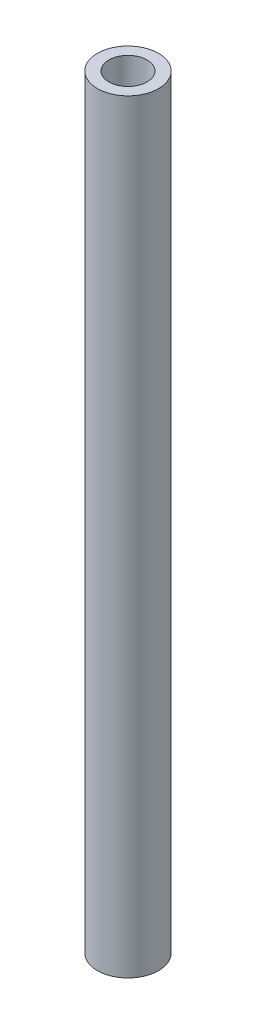
SolidWorks part; units mm, degrees
material "Thornel Mat VMA"
ref_plane "Front Plane" through (0, 0, 0) normal (0, 0, 1) x (1, 0, 0)
ref_plane "Top Plane" through (0, 0, 0) normal (0, 1, 0) x (1, 0, 0)
ref_plane "Right Plane" through (0, 0, 0) normal (1, 0, 0) x (0, 0, -1)
sketch "Sketch1" plane through (0, 0, 0) normal (0, 1, 0) x (1, 0, 0)
  circle A0 centre (0, 0) radius 4
  circle A1 centre (0, 0) radius 2.5
  dimension "D1" = 8
  dimension "D2" = 1.5
extrude "Boss-Extrude1" add sketch "Sketch1" along normal blind 100
